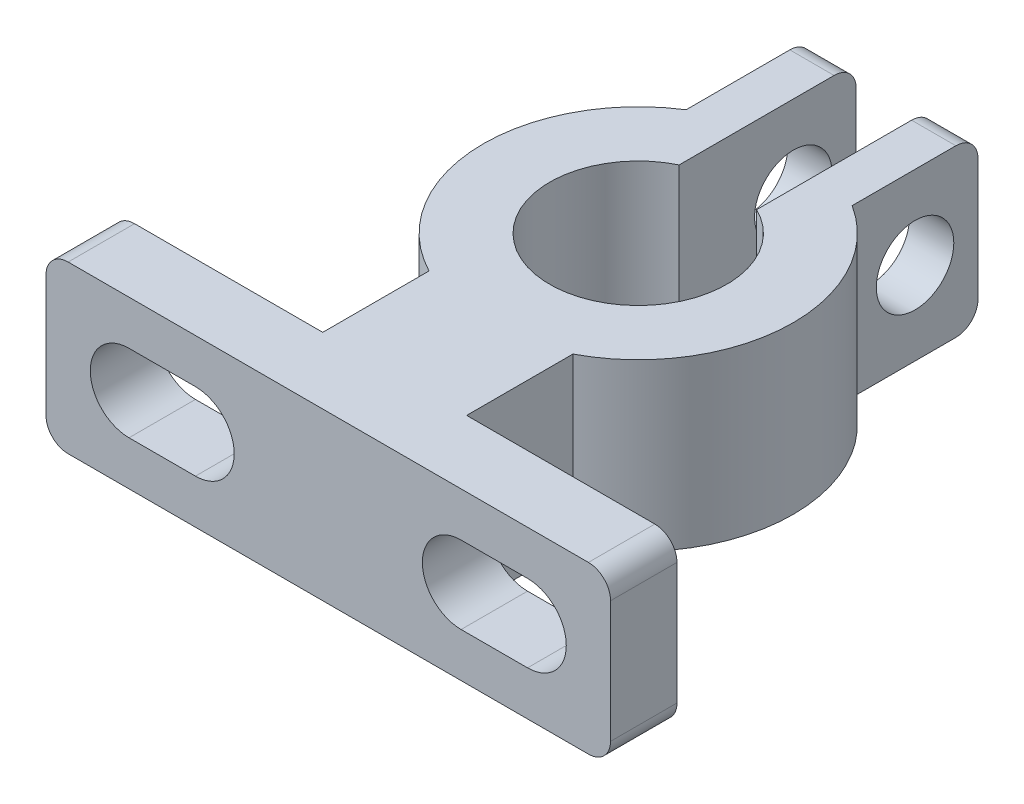
SolidWorks part; units mm, degrees
ref_plane "前视基准面" through (0, 0, 0) normal (0, 0, 1) x (1, 0, 0)
ref_plane "上视基准面" through (0, 0, 0) normal (0, 1, 0) x (1, 0, 0)
ref_plane "右视基准面" through (0, 0, 0) normal (1, 0, 0) x (0, 0, -1)
sketch "草图1" plane through (0, 0, 0) normal (0, 0, 1) x (1, 0, 0)
  line L0 (-9, 0) -> (-6, 0) construction
  line L1 (-12.75, -3.75) -> (12.75, -3.75)
  line L2 (-12.75, -3.75) -> (-12.75, 3.75)
  line L3 (-12.75, 3.75) -> (12.75, 3.75)
  line L4 (12.75, -3.75) -> (12.75, 3.75)
  line L5 (-12.75, -3.75) -> (12.75, 3.75) construction
  line L6 (-12.75, 3.75) -> (12.75, -3.75) construction
  line L7 (-9, 1.75) -> (-6, 1.75)
  line L8 (-9, -1.75) -> (-6, -1.75)
  line L9 (-7.5, 0) -> (7.5, 0) construction
  line L10 (0, 3.75) -> (0, -3.75) construction
  line L11 (6, 0) -> (9, 0) construction
  line L12 (6, 1.75) -> (9, 1.75)
  line L13 (6, -1.75) -> (9, -1.75)
  arc A0 (-9, 1.75) -> (-9, -1.75) centre (-9, 0) ccw
  arc A1 (-6, -1.75) -> (-6, 1.75) centre (-6, 0) ccw
  arc A2 (6, 1.75) -> (6, -1.75) centre (6, 0) ccw
  arc A3 (9, -1.75) -> (9, 1.75) centre (9, 0) ccw
  point P0 (0, 0)
  point P8 (-7.5, 0)
  point P15 (-10.75, 0)
  point P20 (7.5, 0)
  dimension "D1" = 1.75
  dimension "D6" = 1.75
  dimension "D2" = 15
  dimension "D3" = 2
  dimension "D4" = 3
  dimension "D5" = 2
  dimension "D7" = 3
extrude "凸台-拉伸1" add sketch "草图1" along normal blind 3
sketch "草图2" plane through (0, 0, 0) normal (0, 0, -1) x (-1, 0, 0)
  line L0 (12.75, -3.75) -> (-12.75, -3.75) construction
  line L1 (-3.25, 3.75) -> (3.25, 3.75)
  line L2 (-3.25, 3.75) -> (-3.25, -3.75)
  line L3 (-3.25, -3.75) -> (3.25, -3.75)
  line L4 (3.25, 3.75) -> (3.25, -3.75)
  line L5 (-3.25, 3.75) -> (3.25, -3.75) construction
  line L6 (-3.25, -3.75) -> (3.25, 3.75) construction
  arc A0 (-6, -1.75) -> (-6, 1.75) centre (-6, 0) ccw construction
  point P0 (0, 0)
  point P8 (-4.25, 0)
  dimension "D1" = 1
extrude "凸台-拉伸2" add sketch "草图2" along normal blind 7
sketch "草图3" plane through (0, 0, 0) normal (0, 1, 0) x (1, 0, 0)
  line L0 (-3.25, 7) -> (3.25, 7) construction
  line L1 (0, 15) -> (0, 7) construction
  line L2 (-3.75, 22.5969) -> (-1.75, 22.5969)
  line L3 (-3.75, 22.5969) -> (-3.75, 14.5969)
  line L4 (-3.75, 14.5969) -> (-1.75, 14.5969)
  line L5 (-1.75, 22.5969) -> (-1.75, 14.5969)
  line L6 (-3.75, 22.5969) -> (-1.75, 14.5969) construction
  line L7 (-3.75, 14.5969) -> (-1.75, 22.5969) construction
  line L8 (3.75, 14.5969) -> (1.75, 22.5969) construction
  line L9 (3.75, 22.5969) -> (1.75, 14.5969) construction
  line L10 (1.75, 22.5969) -> (1.75, 14.5969)
  line L11 (3.75, 14.5969) -> (1.75, 14.5969)
  line L12 (3.75, 22.5969) -> (3.75, 14.5969)
  line L13 (3.75, 22.5969) -> (1.75, 22.5969)
  circle A0 centre (0, 11) radius 4
  circle A1 centre (0, 11) radius 7
  point P6 (-2.75, 18.5969)
  point P17 (2.75, 18.5969)
  dimension "D1" = 8
  dimension "D2" = 3
  dimension "D3" = 3.5
  dimension "D4" = 2
  dimension "D5" = 8
extrude "凸台-拉伸3" add sketch "草图3" along normal mid plane 7.5 contours L3 A1 L12 L11 A0 L4 | L5 A1 L3 L4 | A1 L5 L2 L3 | A1 L12 L13 L10 | L12 A1 L10 L11
sketch "草图4" plane through (3.75, 0, 0) normal (1, 0, 0) x (0, 0, -1)
  line L0 (16.9108, 3.75) -> (22.5969, 3.75) construction
  line L1 (19.7538, 3.75) -> (19.7538, -3.75) construction
  line L2 (22.5969, -3.75) -> (16.9108, -3.75) construction
  circle A0 centre (19.7538, 0) radius 1.75
  dimension "D1" = 3.5
extrude "切除-拉伸1" cut sketch "草图4" against normal through all
fillet "圆角1" radius 1 8 edges at (2.75, -3.75, -22.5969) (2.75, 3.75, -22.5969) (-2.75, -3.75, -22.5969) (-2.75, 3.75, -22.5969) (-12.75, -3.75, 1.5) (12.75, -3.75, 1.5) (12.75, 3.75, 1.5) (-12.75, 3.75, 1.5)
